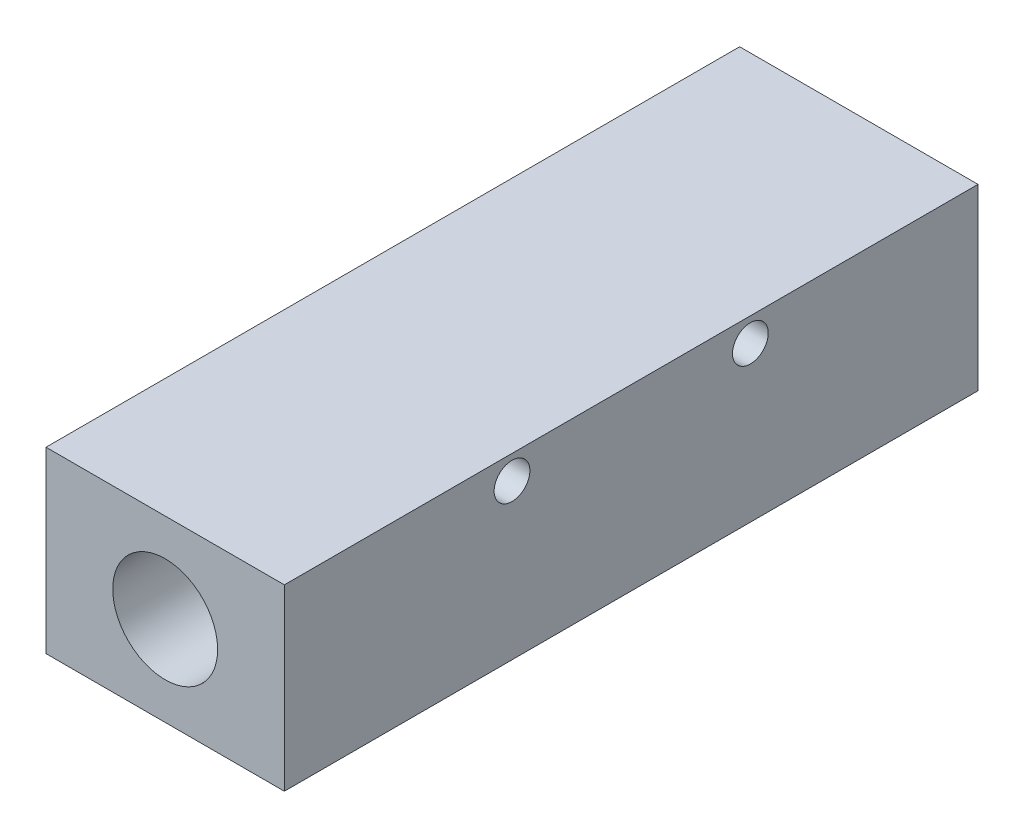
SolidWorks part; units mm, degrees
material "6063-T5"
ref_plane "Piano frontale" through (0, 0, 0) normal (0, 0, 1) x (1, 0, 0)
ref_plane "Piano superiore" through (0, 0, 0) normal (0, 1, 0) x (1, 0, 0)
ref_plane "Piano destro" through (0, 0, 0) normal (1, 0, 0) x (0, 0, -1)
sketch "Schizzo1" plane through (0, 0, 0) normal (0, 0, 1) x (1, 0, 0)
  line L1 (10, -7.5) -> (-10, -7.5)
  line L2 (10, -7.5) -> (10, 7.5)
  line L3 (10, 7.5) -> (-10, 7.5)
  line L4 (-10, -7.5) -> (-10, 7.5)
  line L5 (10, -7.5) -> (-10, 7.5) construction
  line L6 (10, 7.5) -> (-10, -7.5) construction
  point P0 (0, 0)
  dimension "D1" = 15
  dimension "D2" = 20
extrude "Estrusione-Estrusione1" add sketch "Schizzo1" against normal blind 58.2
sketch "Schizzo2" plane through (0, 0, -58.2) normal (0, 0, -1) x (-1, 0, 0)
  circle A0 centre (0, 0) radius 3
  dimension "D1" = 6
extrude "Taglio-Estrusione1" cut sketch "Schizzo2" against normal through all
sketch "Schizzo3" plane through (0, 0, -58.2) normal (0, 0, -1) x (-1, 0, 0)
  circle A0 centre (0, 0) radius 6.75
  dimension "D1" = 13.5
extrude "Taglio-Estrusione2" cut sketch "Schizzo3" against normal blind 13
sketch "Schizzo4" plane through (10, 0, 0) normal (1, 0, 0) x (0, 0, -1)
  line L0 (0, 5.5) -> (58.2, 5.5) construction
  line L1 (0, -7.5) -> (0, 7.5) construction
  line L2 (58.2, -7.5) -> (58.2, 7.5) construction
  line L3 (58.2, 7.5) -> (0, 7.5) construction
  line L4 (29.1, 7.5) -> (29.1, -7.5) construction
  line L5 (58.2, -7.5) -> (0, -7.5) construction
  circle A0 centre (19.1, 5.5) radius 1.5
  circle A1 centre (39.1, 5.5) radius 1.5
  dimension "D2" = 3
  dimension "D1" = 2
  dimension "D3" = 10
extrude "Taglio-Estrusione3" cut sketch "Schizzo4" against normal through all
hole_wizard "Foro filettato G1/8-1" positions "Schizzo8" profile "Schizzo7" tap size "G1/8" standard "BSI"
sketch "Schizzo8" plane through (0, 0, 0) normal (0, 0, 1) x (1, 0, 0)
  point P0 (0, 0)
sketch "Schizzo7" plane through (0, 0, 0) normal (1, 0, 0) x (0, -1, 0)
  line L0 (0, 0) -> (0, 15.3638)
  line L1 (0, 15.3638) -> (4.4, 12.72)
  line L2 (4.4, 12.72) -> (4.4, 0)
  line L5 (4.4, 0) -> (0, 0)
  line L10 (0, 15.3638) -> (-4.4, 12.72) construction
  line L11 (0, -6.35) -> (0, 107.95) construction
  dimension "Tap Drill Dia." = 8.8
  dimension "Tap Drill Depth" = 12.72
  dimension "Drill Angle" = 118
